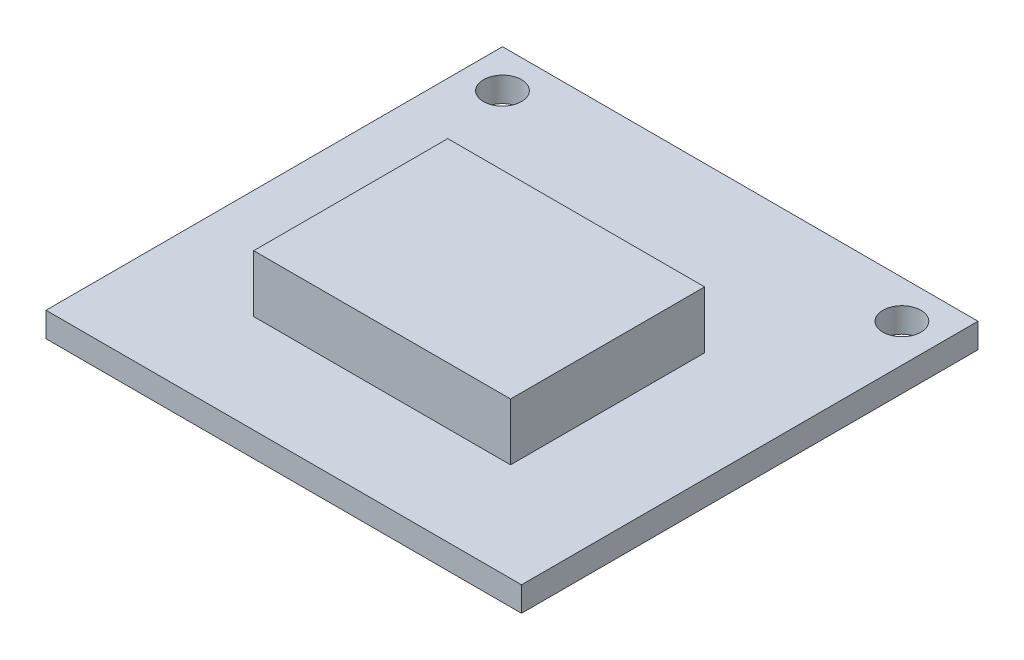
SolidWorks part; units mm, degrees
ref_plane "Front Plane" through (0, 0, 0) normal (0, 0, 1) x (1, 0, 0)
ref_plane "Top Plane" through (0, 0, 0) normal (0, 1, 0) x (1, 0, 0)
ref_plane "Right Plane" through (0, 0, 0) normal (1, 0, 0) x (0, 0, -1)
sketch "Sketch1" plane through (0, 0, 0) normal (0, 1, 0) x (1, 0, 0)
  line L0 (0, 13.515) -> (0, -16.9186) construction
  line L1 (-12.5, 12) -> (12.5, 12)
  line L2 (-12.5, 12) -> (-12.5, -12)
  line L3 (-12.5, -12) -> (12.5, -12)
  line L4 (12.5, 12) -> (12.5, -12)
  line L5 (-12.5, 12) -> (12.5, -12) construction
  line L6 (-12.5, -12) -> (12.5, 12) construction
  circle A0 centre (10.5, 10) radius 1
  circle A1 centre (-10.5, 10) radius 1
  point P0 (0, 0)
  dimension "D3" = 2
  dimension "D4" = 2
  dimension "D1" = 25
  dimension "D2" = 24
  dimension "D5" = 2
extrude "Boss-Extrude1" add sketch "Sketch1" along normal blind 1.3
sketch "Sketch2" plane through (0, 1.3, 0) normal (0, 1, 0) x (1, 0, 0)
  line L1 (-6.7514, 3.3757) -> (6.7514, 3.3757)
  line L2 (-6.7514, 3.3757) -> (-6.7514, -6.8287)
  line L3 (-6.7514, -6.8287) -> (6.7514, -6.8287)
  line L4 (6.7514, 3.3757) -> (6.7514, -6.8287)
  line L5 (-6.7514, 3.3757) -> (6.7514, -6.8287) construction
  line L6 (-6.7514, -6.8287) -> (6.7514, 3.3757) construction
  point P0 (0, -1.7265)
  dimension "D1" = 0
extrude "Boss-Extrude2" add sketch "Sketch2" along normal blind 3
